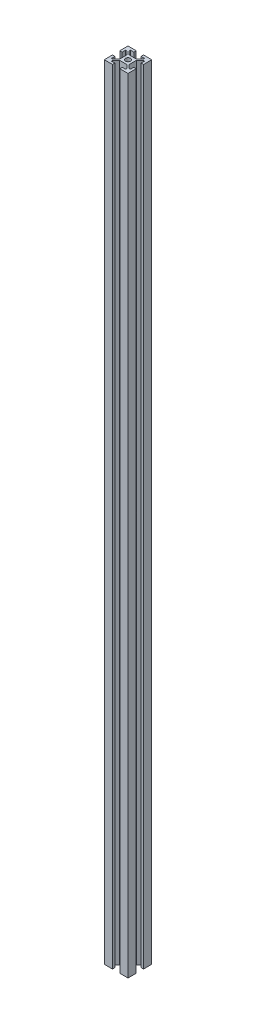
SolidWorks part; units mm, degrees
ref_plane "Front" through (0, 0, 0) normal (0, 0, 1) x (1, 0, 0)
ref_plane "Top" through (0, 0, 0) normal (0, 1, 0) x (1, 0, 0)
ref_plane "Right" through (0, 0, 0) normal (1, 0, 0) x (0, 0, -1)
sketch "스케치1" plane through (0, 0, 0) normal (0, 1, 0) x (1, 0, 0)
  line L0 (3.1, 8) -> (6, 8)
  line L1 (-10.001, 9.999) -> (-3.1, 9.999)
  line L2 (-10.001, 9.999) -> (-10.001, 3.1)
  line L3 (-10.001, -9.999) -> (-3.1, -9.999)
  line L4 (10.001, 9.999) -> (10.001, 3.1)
  line L5 (-10.001, 9.999) -> (-1.5204, 1.5201) construction
  line L6 (-10.001, -9.999) -> (-1.5204, -1.5201) construction
  line L11 (-7, -7) -> (-1.5203, -1.5203) construction
  line L12 (-7, 7) -> (-1.5203, 1.5203) construction
  line L15 (-3.1, 9.999) -> (-3.1, 8)
  line L17 (3.1, 9.999) -> (3.1, 8)
  line L18 (8, -3.1) -> (8, -6)
  line L27 (-3.1, 8) -> (-6, 8)
  line L28 (6, 8) -> (6, 7)
  line L30 (0, 4) -> (3, 4)
  line L31 (3, 4) -> (6, 7)
  line L32 (-6, 8) -> (-6, 7)
  line L33 (-6, 7) -> (-3, 4)
  line L34 (0, 4) -> (-3, 4)
  line L35 (3.1, 9.999) -> (10.001, 9.999)
  line L36 (10.001, 3.1) -> (8, 3.1)
  line L37 (10.001, -3.1) -> (8, -3.1)
  line L38 (8, 3.1) -> (8, 6)
  line L39 (8, -6) -> (7, -6)
  line L40 (4, 0) -> (4, -3)
  line L41 (4, -3) -> (7, -6)
  line L42 (8, 6) -> (7, 6)
  line L43 (7, 6) -> (4, 3)
  line L44 (4, 0) -> (4, 3)
  line L45 (-3.1, -8) -> (-6, -8)
  line L47 (3.1, -9.999) -> (3.1, -8)
  line L48 (-3.1, -9.999) -> (-3.1, -8)
  line L49 (3.1, -8) -> (6, -8)
  line L50 (-6, -8) -> (-6, -7)
  line L51 (0, -4) -> (-3, -4)
  line L52 (-3, -4) -> (-6, -7)
  line L53 (6, -8) -> (6, -7)
  line L54 (6, -7) -> (3, -4)
  line L55 (0, -4) -> (3, -4)
  line L56 (-8, 3.1) -> (-8, 6)
  line L58 (-10.001, -3.1) -> (-8, -3.1)
  line L59 (-10.001, 3.1) -> (-8, 3.1)
  line L60 (-8, -3.1) -> (-8, -6)
  line L61 (-8, 6) -> (-7, 6)
  line L62 (-4, 0) -> (-4, 3)
  line L63 (-4, 3) -> (-7, 6)
  line L64 (-8, -6) -> (-7, -6)
  line L65 (-7, -6) -> (-4, -3)
  line L66 (-4, 0) -> (-4, -3)
  line L67 (-10.001, -3.1) -> (-10.001, -9.999)
  line L69 (3.1, -9.999) -> (10.001, -9.999)
  line L72 (10.001, -3.1) -> (10.001, -9.999)
  line L73 (1.5203, -1.5203) -> (7, -7) construction
  line L74 (1.5204, -1.5201) -> (10.001, -9.999) construction
  line L75 (1.5203, 1.5203) -> (7, 7) construction
  line L76 (1.5204, 1.5201) -> (10.001, 9.999) construction
  circle A4 centre (0, 0) radius 2.15
  point P0 (0, 0)
  point P6 (0, 0)
  point P21 (0, 0)
  point P22 (0, 10)
  point P31 (0, 0)
  point P40 (10, 0)
  point P46 (0, 0)
  point P53 (0, -10)
  point P59 (0, 0)
  point P66 (-10, 0)
  point P72 (0, 0)
  dimension "D1" = 4
extrude "보스-돌출1" add sketch "스케치1" along normal blind 659.8
sketch "스케치3" plane through (10.001, 0, 0) normal (1, 0, 0) x (0, 0, -1)
  line L0 (0, 0) -> (0, 659.8) construction
  line L1 (-3, 659.8) -> (3, 659.8) construction
  circle A0 centre (0, 329.9) radius 3
extrude "컷-돌출1" cut sketch "스케치3" against normal blind 26
